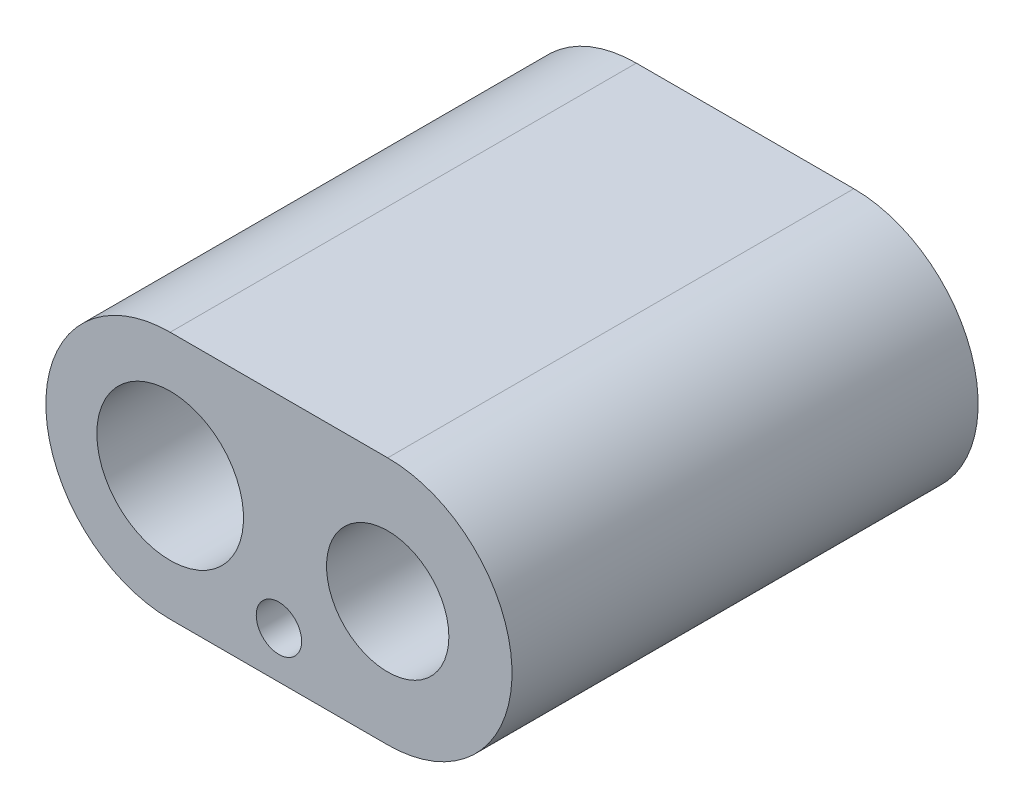
SolidWorks part; units mm, degrees
ref_plane "Front Plane" through (0, 0, 0) normal (0, 0, 1) x (1, 0, 0)
ref_plane "Top Plane" through (0, 0, 0) normal (0, 1, 0) x (1, 0, 0)
ref_plane "Right Plane" through (0, 0, 0) normal (1, 0, 0) x (0, 0, -1)
sketch "Sketch1" plane through (0, 0, 0) normal (0, 0, 1) x (1, 0, 0)
  line L0 (0, 0) -> (8.89, 0) construction
  line L1 (0, 5.08) -> (8.89, 5.08)
  line L2 (0, -5.08) -> (8.89, -5.08)
  line L3 (4.445, 0) -> (4.445, -3.175) construction
  arc A0 (0, 5.08) -> (0, -5.08) centre (0, 0) ccw
  arc A1 (8.89, -5.08) -> (8.89, 5.08) centre (8.89, 0) ccw
  circle A2 centre (0, 0) radius 2.9972
  circle A3 centre (8.89, 0) radius 1.5875
  circle A4 centre (4.445, -3.175) radius 0.9271
  point P3 (4.445, 0)
  dimension "D3" = 1.8542
  dimension "D4" = 3.175
  dimension "D5" = 5.9944
  dimension "D1" = 10.16
  dimension "D2" = 8.89
  dimension "D6" = 8.255
extrude "Boss-Extrude1" add sketch "Sketch1" along normal blind 19.05
sketch "Sketch2" plane through (0, 0, 19.05) normal (0, 0, 1) x (1, 0, 0)
  circle A0 centre (8.89, 0) radius 2.5
  dimension "D1" = 5
extrude "Cut-Extrude1" cut sketch "Sketch2" against normal blind 5
sketch "Sketch3" plane through (0, 0, 0) normal (0, 1, 0) x (1, 0, 0)
  line L0 (11.39, -14.05) -> (10.4775, -13.5017)
  line L1 (10.4775, -14.05) -> (10.4775, 0) construction
  line L2 (10.4775, -13.5017) -> (10.4775, -14.05)
  line L3 (10.4775, -14.05) -> (11.39, -14.05)
  line L4 (8.89, -14.05) -> (8.89, -16.1427) construction
  line L5 (7.3025, -14.05) -> (10.4775, -14.05) construction
  line L6 (8.89, -19.05) -> (8.89, 0) construction
  dimension "D1" = 31
revolve "Cut-Revolve1" cut sketch "Sketch3" angle 360 about L4
